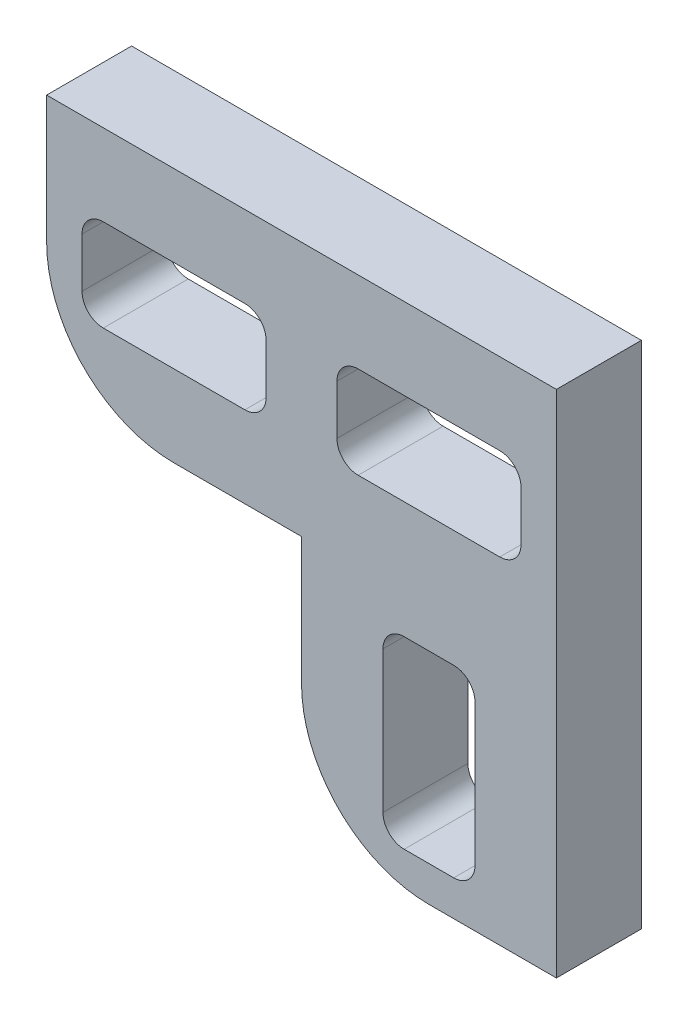
SolidWorks part; units mm, degrees
ref_plane "Alzado" through (0, 0, 0) normal (0, 0, 1) x (1, 0, 0)
ref_plane "Planta" through (0, 0, 0) normal (0, 1, 0) x (1, 0, 0)
ref_plane "Vista lateral" through (0, 0, 0) normal (1, 0, 0) x (0, 0, -1)
sketch "Model" plane through (0, 0, 0) normal (0, 0, 1) x (1, 0, 0)
  line L0 (149.3421, 211.824) -> (158.3421, 211.824)
  line L1 (153.8421, 202.824) -> (149.3421, 202.824)
  line L2 (162.8421, 198.324) -> (162.8421, 211.824)
  line L3 (153.8421, 198.324) -> (153.8421, 202.824)
  line L4 (156.7171, 195.824) -> (156.7171, 200.824)
  line L5 (157.4671, 201.574) -> (159.2171, 201.574)
  line L6 (159.9671, 200.824) -> (159.9671, 195.824)
  line L7 (159.2171, 195.074) -> (157.4671, 195.074)
  line L8 (151.8421, 205.699) -> (146.8421, 205.699)
  line L9 (146.0921, 206.449) -> (146.0921, 208.199)
  line L10 (146.8421, 208.949) -> (151.8421, 208.949)
  line L11 (152.5921, 208.199) -> (152.5921, 206.449)
  line L12 (160.8421, 205.699) -> (155.8421, 205.699)
  line L13 (155.0921, 206.449) -> (155.0921, 208.199)
  line L14 (155.8421, 208.949) -> (160.8421, 208.949)
  line L15 (161.5921, 208.199) -> (161.5921, 206.449)
  line L16 (149.3421, 211.824) -> (144.8421, 211.824)
  line L17 (158.3421, 211.824) -> (162.8421, 211.824)
  line L18 (144.8421, 207.324) -> (144.8421, 211.824)
  line L19 (162.8421, 198.324) -> (162.8421, 193.824)
  line L20 (158.3421, 193.824) -> (162.8421, 193.824)
  arc A0 (144.8421, 207.324) -> (149.3421, 202.824) centre (149.3421, 207.324) ccw
  arc A1 (153.8421, 198.324) -> (158.3421, 193.824) centre (158.3421, 198.324) ccw
  arc A2 (157.4671, 201.574) -> (156.7171, 200.824) centre (157.4671, 200.824) ccw
  arc A3 (159.9671, 200.824) -> (159.2171, 201.574) centre (159.2171, 200.824) ccw
  arc A4 (159.2171, 195.074) -> (159.9671, 195.824) centre (159.2171, 195.824) ccw
  arc A5 (156.7171, 195.824) -> (157.4671, 195.074) centre (157.4671, 195.824) ccw
  arc A6 (146.0921, 206.449) -> (146.8421, 205.699) centre (146.8421, 206.449) ccw
  arc A7 (146.8421, 208.949) -> (146.0921, 208.199) centre (146.8421, 208.199) ccw
  arc A8 (152.5921, 208.199) -> (151.8421, 208.949) centre (151.8421, 208.199) ccw
  arc A9 (151.8421, 205.699) -> (152.5921, 206.449) centre (151.8421, 206.449) ccw
  arc A10 (155.0921, 206.449) -> (155.8421, 205.699) centre (155.8421, 206.449) ccw
  arc A11 (155.8421, 208.949) -> (155.0921, 208.199) centre (155.8421, 208.199) ccw
  arc A12 (161.5921, 208.199) -> (160.8421, 208.949) centre (160.8421, 208.199) ccw
  arc A13 (160.8421, 205.699) -> (161.5921, 206.449) centre (160.8421, 206.449) ccw
extrude "Saliente-Extruir1" add sketch "Model" along normal blind 3
